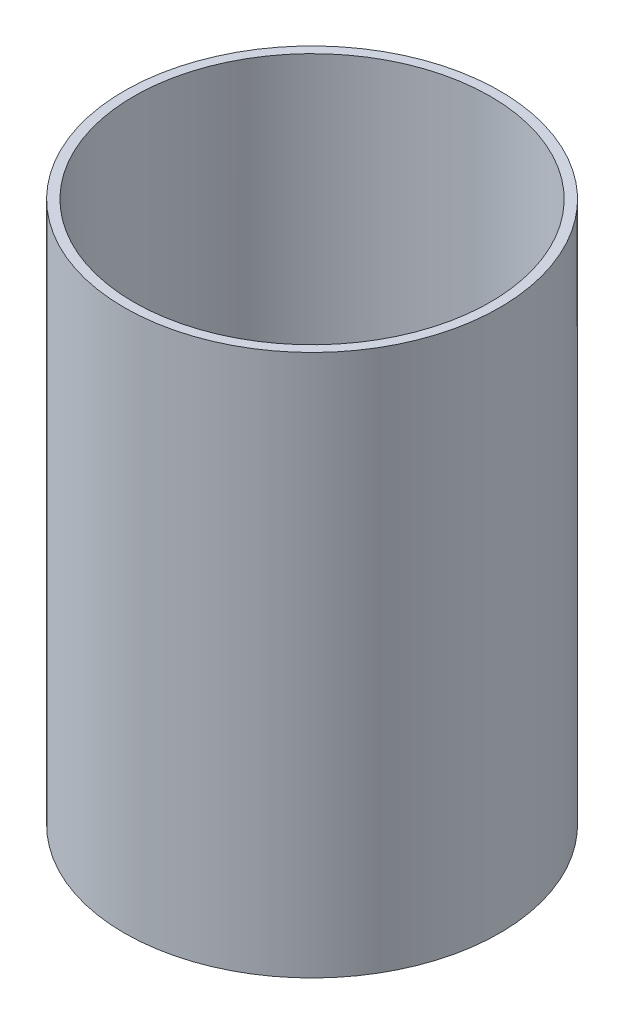
SolidWorks part; units mm, degrees
ref_plane "Front Plane" through (0, 0, 0) normal (0, 0, 1) x (1, 0, 0)
ref_plane "Top Plane" through (0, 0, 0) normal (0, 1, 0) x (1, 0, 0)
ref_plane "Right Plane" through (0, 0, 0) normal (1, 0, 0) x (0, 0, -1)
sketch "Sketch1" plane through (0, 0, 0) normal (0, 1, 0) x (1, 0, 0)
  circle A0 centre (0, 0) radius 50.546
  circle A2 centre (0, 0) radius 48.006
  dimension "D1" = 2.54
  dimension "D2" = 101.092
extrude "Boss-Extrude1" add sketch "Sketch1" along normal blind 145.8595
sketch "Sketch2" plane through (0, 0, 0) normal (0, -1, 0) x (1, 0, 0)
  circle A0 centre (0, 0) radius 50.546
  circle A1 centre (0, 0) radius 50.546 construction
extrude "Boss-Extrude2" add sketch "Sketch2" against normal blind 1.9812
sketch "Sketch3" plane through (0, 1.9812, 0) normal (0, 1, 0) x (-1, 0, 0)
  circle A0 centre (0, 28.575) radius 14.605
  point P2 (0, 0)
  point P4 (1.8596, -28.5144)
  point P5 (-5.1818, 28.1012)
  dimension "D1" = 29.21
  dimension "D2" = 28.575
extrude "Cut-Extrude1" cut sketch "Sketch3" against normal through all
